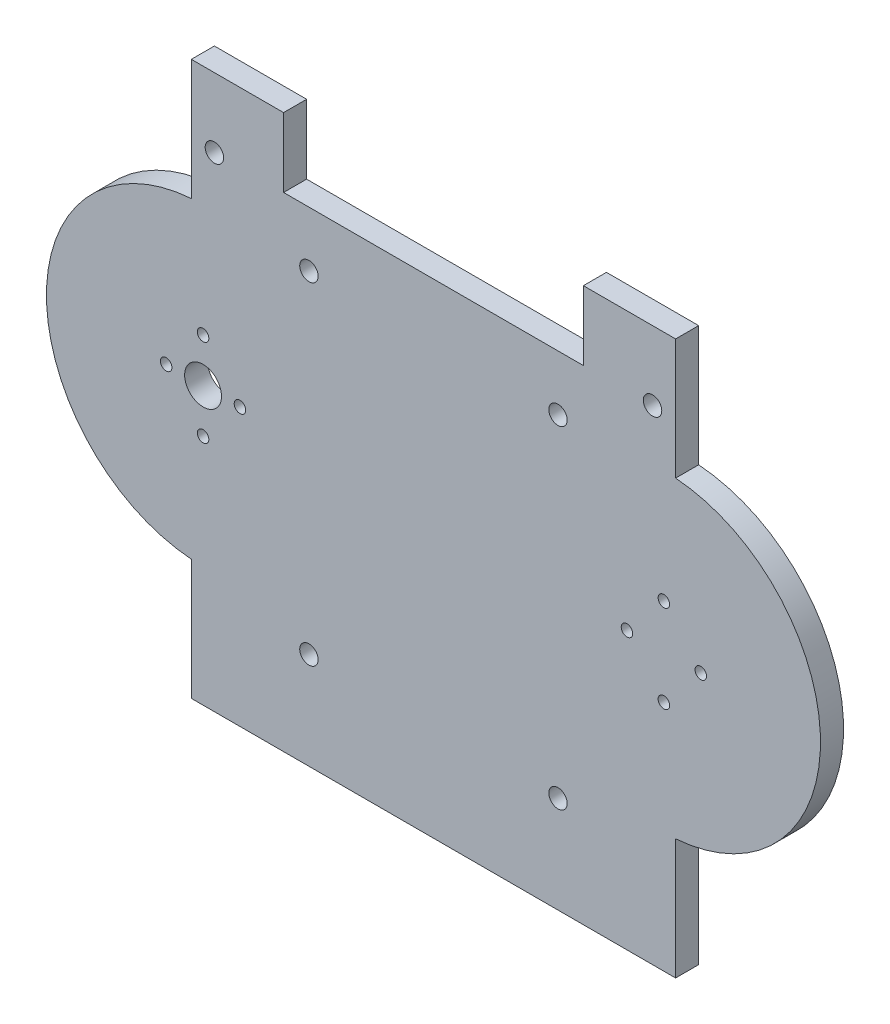
SolidWorks part; units mm, degrees
ref_plane "Front Plane" through (0, 0, 0) normal (0, 0, 1) x (1, 0, 0)
ref_plane "Top Plane" through (0, 0, 0) normal (0, 1, 0) x (1, 0, 0)
ref_plane "Right Plane" through (0, 0, 0) normal (1, 0, 0) x (0, 0, -1)
sketch "Sketch1" plane through (0, 0, 0) normal (0, 0, 1) x (1, 0, 0)
  line L0 (-49.9562, 0) -> (49.9562, 0) construction
  line L1 (-100, -75) -> (100, -75)
  line L2 (-100, -75) -> (-100, 75)
  line L3 (-100, 75) -> (100, 75)
  line L4 (100, -75) -> (100, 75)
  line L5 (-100, -75) -> (100, 75) construction
  line L6 (-100, 75) -> (100, -75) construction
  line L7 (-19, 0) -> (19, 0) construction
  line L8 (-47.5, 45) -> (47.5, 45) construction
  line L9 (0, 75) -> (0, -75) construction
  line L10 (-27, -39) -> (27, -39) construction
  line L11 (-27, -39) -> (-27, 33) construction
  line L12 (-27, 33) -> (27, 33) construction
  line L13 (27, -39) -> (27, 33) construction
  line L14 (-27, -39) -> (27, 33) construction
  line L15 (-27, 33) -> (27, -39) construction
  line L16 (-49.9562, -9.5) -> (-57.9562, 0) construction
  line L17 (-49.9562, -9.5) -> (-41.9562, 0) construction
  line L18 (-41.9562, 0) -> (-49.9562, 9.5) construction
  line L19 (-57.9562, 0) -> (-49.9562, 9.5) construction
  line L20 (-49.9562, -9.5) -> (-49.9562, 9.5) construction
  line L21 (-41.9562, 0) -> (-57.9562, 0) construction
  line L23 (-52.5, 60) -> (52.5, 60)
  line L24 (-52.5, 60) -> (-52.5, -60)
  line L25 (-52.5, -60) -> (52.5, -60)
  line L26 (52.5, 60) -> (52.5, -60)
  line L27 (-52.5, 60) -> (52.5, -60) construction
  line L28 (-52.5, -60) -> (52.5, 60) construction
  line L29 (-32.5, 60) -> (32.5, 60)
  line L30 (-32.5, 60) -> (-32.5, 45)
  line L31 (-32.5, 45) -> (32.5, 45)
  line L32 (32.5, 60) -> (32.5, 45)
  line L33 (-32.5, 60) -> (32.5, 45) construction
  line L34 (-32.5, 45) -> (32.5, 60) construction
  circle A0 centre (-49.9562, 0) radius 30.9562 construction
  circle A1 centre (49.9562, 0) radius 30.9563 construction
  circle A2 centre (-47.5, 45) radius 2
  circle A3 centre (47.5, 45) radius 2
  circle A4 centre (-27, 33) radius 2
  circle A5 centre (27, 33) radius 2
  circle A6 centre (27, -39) radius 2
  circle A7 centre (-27, -39) radius 2
  circle A8 centre (-49.9562, 9.5) radius 1.25
  circle A9 centre (-41.9562, 0) radius 1.25
  circle A10 centre (-49.9562, -9.5) radius 1.25
  circle A11 centre (-57.9562, 0) radius 1.25
  circle A12 centre (49.9562, 9.5) radius 1.25
  circle A13 centre (57.9562, 0) radius 1.25
  circle A14 centre (41.9562, 0) radius 1.25
  circle A15 centre (49.9562, -9.5) radius 1.25
  circle A16 centre (-49.9562, 0) radius 4
  circle A17 centre (-49.9562, 0) radius 33.9562
  circle A18 centre (49.9562, 0) radius 33.9563
  point P0 (0, 0)
  point P8 (0, 0)
  point P15 (0, 45)
  point P18 (0, -3)
  point P36 (-49.9562, 0)
  point P38 (-49.9562, 0)
  point P56 (0, 0)
  point P57 (0, 0)
  point P63 (0, 52.5)
  dimension "D3" = 61.9125
  dimension "D4" = 38
  dimension "D5" = 4
  dimension "D8" = 4
  dimension "D11" = 2.5
  dimension "D12" = 8
  dimension "D1" = 150
  dimension "D2" = 200
  dimension "D6" = 72
  dimension "D7" = 54
  dimension "D9" = 16
  dimension "D10" = 19
  dimension "D14" = 15
  dimension "D15" = 120
  dimension "D16" = 105
  dimension "D17" = 95
  dimension "D18" = 12
  dimension "D19" = 15
  dimension "D20" = 65
  dimension "D13" = 3
extrude "Boss-Extrude1" add sketch "Sketch1" along normal blind 5 contours A18 L26 L23 L24 A17 L25 A2 A3 A4 A5 A6 A7 | L24 A17 A11 A10 A8 A16 | L24 A17 A9 | L26 A18 A15 A12 A13 | L26 A18 A14
